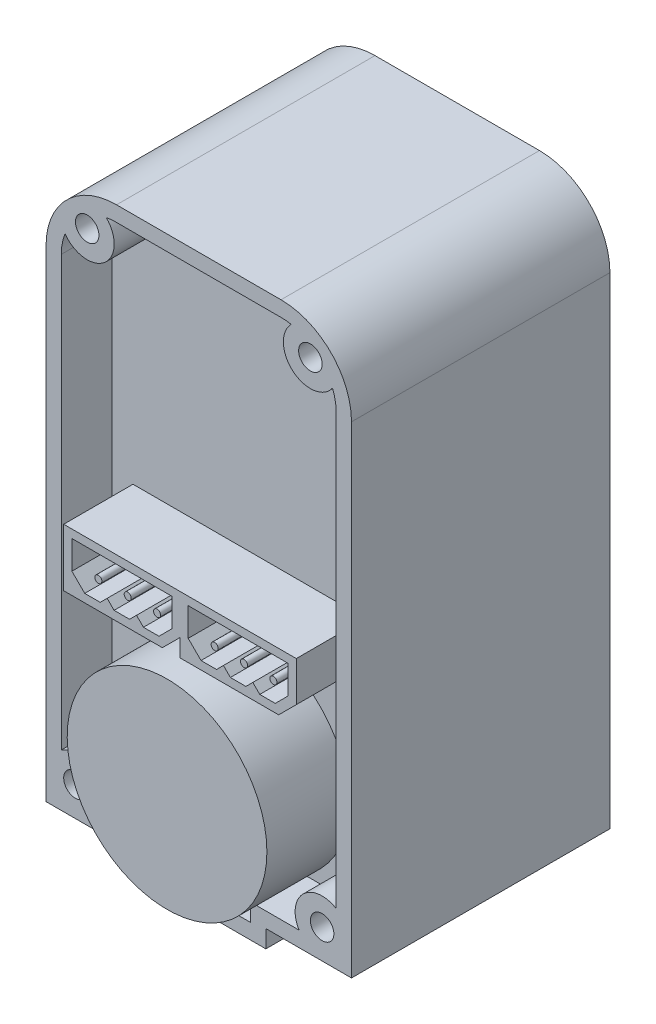
SolidWorks part; units mm, degrees
ref_plane "Front Plane" through (0, 0, 0) normal (0, 0, 1) x (1, 0, 0)
ref_plane "Top Plane" through (0, 0, 0) normal (0, 1, 0) x (1, 0, 0)
ref_plane "Right Plane" through (0, 0, 0) normal (1, 0, 0) x (0, 0, -1)
sketch "Sketch1" plane through (0, 0, 0) normal (0, 0, 1) x (1, 0, 0)
  line L0 (0, -55) -> (0, 55) construction
  line L1 (-7, 26.5) -> (7, 26.5)
  line L2 (-13, 20.5) -> (-13, -20.5)
  line L3 (-13, -20.5) -> (-5.71, -20.5)
  line L4 (13, 20.5) -> (13, -20.5)
  line L5 (55, 0) -> (-55, 0) construction
  line L6 (5.71, -20.5) -> (13, -20.5)
  line L8 (-5.71, -20.5) -> (-5.71, -22)
  line L9 (-5.71, -22) -> (5.71, -22)
  line L10 (5.71, -20.5) -> (5.71, -22)
  arc A0 (13, 20.5) -> (7, 26.5) centre (7, 20.5) ccw
  arc A1 (-7, 26.5) -> (-13, 20.5) centre (-7, 20.5) ccw
  point P4 (0, 26.5)
  point P9 (13, 0)
  point P14 (0, -22)
  point P18 (13, 26.5)
  point P21 (-13, 26.5)
  dimension "D5" = 6
  dimension "D1" = 26
  dimension "D2" = 47
  dimension "D3" = 1.5
  dimension "D4" = 11.42
extrude "Boss-Extrude1" add sketch "Sketch1" along normal mid plane 22
sketch "Sketch2" plane through (0, 0, 11) normal (0, 0, 1) x (1, 0, 0)
  line L0 (-9.5, 23.5) -> (9.5, 23.5) construction
  line L1 (-10.5, -18) -> (10.5, -18) construction
  line L2 (0, -55) -> (0, 55) construction
  line L3 (7, 26.5) -> (-7, 26.5) construction
  circle A0 centre (-9.5, 23.5) radius 1
  circle A1 centre (-10.5, -18) radius 1
  circle A2 centre (10.5, -18) radius 1
  circle A3 centre (9.5, 23.5) radius 1
  point P8 (0, 23.5)
  point P11 (0, -18)
  dimension "D3" = 2
  dimension "D1" = 19
  dimension "D2" = 21
  dimension "D4" = 3
  dimension "D5" = 41.5
extrude "Cut-Extrude1" cut sketch "Sketch2" against normal through all
sketch "Sketch4" plane through (0, 0, 11) normal (0, 0, 1) x (1, 0, 0)
  line L16 (4.41, -19.2) -> (11.7, -19.2)
  line L17 (11.7, -19.2) -> (11.7, 20.5)
  line L18 (7, 25.2) -> (-7, 25.2)
  line L19 (-11.7, 20.5) -> (-11.7, -19.2)
  line L20 (-11.7, -19.2) -> (-4.41, -19.2)
  line L21 (-4.41, -19.2) -> (-4.41, -20.7)
  line L22 (-4.41, -20.7) -> (4.41, -20.7)
  line L23 (4.41, -20.7) -> (4.41, -19.2)
  line L32 (4.41, -19.2) -> (8.5379, -19.2)
  line L33 (11.7, -16.0379) -> (11.7, 20.5)
  line L34 (7, 25.2) -> (-7, 25.2)
  line L35 (-11.7, 20.5) -> (-11.7, -16.0379)
  line L36 (-8.5379, -19.2) -> (-4.41, -19.2)
  line L37 (-4.41, -19.2) -> (-4.41, -20.7)
  line L38 (-4.41, -20.7) -> (4.41, -20.7)
  line L39 (4.41, -20.7) -> (4.41, -19.2)
  arc A16 (11.7, 20.5) -> (7, 25.2) centre (7, 20.5) ccw
  arc A17 (-7, 25.2) -> (-11.7, 20.5) centre (-7, 20.5) ccw
  arc A18 (11.7, 20.5) -> (11.3874, 22.1855) centre (7, 20.5) ccw
  arc A19 (-7, 25.2) -> (-7.8667, 25.1194) centre (-7, 20.5) ccw
  circle A20 centre (-9.5, 23.5) radius 2.3
  arc A21 (-11.3874, 22.1855) -> (-7.8667, 25.1194) centre (-9.5, 23.5) ccw
  circle A23 centre (9.5, 23.5) radius 2.3
  arc A24 (7.8667, 25.1194) -> (11.3874, 22.1855) centre (9.5, 23.5) ccw
  circle A29 centre (-10.5, -18) radius 2.3
  arc A30 (-8.5379, -19.2) -> (-11.7, -16.0379) centre (-10.5, -18) ccw
  arc A31 (-11.3874, 22.1855) -> (-11.7, 20.5) centre (-7, 20.5) ccw
  circle A32 centre (10.5, -18) radius 2.3
  arc A33 (11.7, -16.0379) -> (8.5379, -19.2) centre (10.5, -18) ccw
  arc A34 (7.8667, 25.1194) -> (7, 25.2) centre (7, 20.5) ccw
  dimension "D1" = 1.3
  dimension "D2" = 1.3
  dimension "D3" = 1.3
  dimension "D4" = 1.3
  dimension "D5" = 1.3
extrude "Cut-Extrude2" cut sketch "Sketch4" against normal blind 4.3
sketch "Sketch6" plane through (0, 0, 6.7) normal (0, 0, 1) x (1, 0, 0)
  line L0 (0, -12.1) -> (0, 12.1) construction
  line L1 (-5.71, -22) -> (5.71, -22) construction
  circle A0 centre (0, -12.1) radius 8.5
  dimension "D1" = 17
  dimension "D2" = 9.9
extrude "Boss-Extrude2" add sketch "Sketch6" along normal blind 7
sketch "Sketch7" plane through (0, 0, 6.7) normal (0, 0, 1) x (1, 0, 0)
  line L0 (-1.5, -2.6) -> (0, -1.1)
  line L5 (-9.9, 2.3) -> (9.9, 2.3)
  line L6 (-9.9, 2.3) -> (-9.9, -2.6)
  line L7 (-9.9, -2.6) -> (-1.5, -2.6)
  line L8 (9.9, 2.3) -> (9.9, -1.1)
  line L9 (0, -1.1) -> (0, -2.6)
  line L10 (8.4, -2.6) -> (9.9, -1.1)
  line L11 (0, -2.6) -> (8.4, -2.6)
  line L12 (0, -13.585) -> (0, 13.585) construction
  line L13 (7, 26.5) -> (-7, 26.5) construction
  dimension "D1" = 4.9
  dimension "D2" = 9.9
  dimension "D3" = 45
  dimension "D4" = 24.2
  dimension "D5" = 1.5
extrude "Boss-Extrude3" add sketch "Sketch7" along normal blind 5.9
sketch "Sketch8" plane through (0, 0, 12.6) normal (0, 0, 1) x (1, 0, 0)
  line L0 (-9.2, 1.6) -> (-9.2, -0.8101)
  line L1 (-8.1101, -1.9) -> (-6.7899, -1.9)
  line L2 (-1.7899, -1.9) -> (-0.7, -0.8101)
  line L3 (-0.7, -0.8101) -> (-0.7, 1.6)
  line L4 (-0.7, 1.6) -> (-9.2, 1.6)
  line L5 (9.9, 2.3) -> (-9.9, 2.3) construction
  line L6 (-9.9, 2.3) -> (-9.9, -2.6) construction
  line L7 (0, -1.1) -> (0, -2.6) construction
  line L8 (-1.5, -2.6) -> (0, -1.1) construction
  line L9 (-9.2, -0.8101) -> (-8.1101, -1.9)
  line L10 (-6.7899, -1.9) -> (-6.2, -1.3101)
  line L11 (-6.2, -1.3101) -> (-5.6101, -1.9)
  line L12 (-4.2899, -1.9) -> (-3.7, -1.3101)
  line L13 (-3.7, -1.3101) -> (-3.1101, -1.9)
  line L14 (-3.1101, -1.9) -> (-1.7899, -1.9)
  line L15 (-5.6101, -1.9) -> (-4.2899, -1.9)
  line L16 (0, -2.6) -> (0, 4.1389) construction
  line L17 (5.6101, -1.9) -> (4.2899, -1.9)
  line L18 (3.1101, -1.9) -> (1.7899, -1.9)
  line L19 (3.7, -1.3101) -> (3.1101, -1.9)
  line L20 (4.2899, -1.9) -> (3.7, -1.3101)
  line L21 (6.2, -1.3101) -> (5.6101, -1.9)
  line L22 (6.7899, -1.9) -> (6.2, -1.3101)
  line L23 (9.2, -0.8101) -> (8.1101, -1.9)
  line L24 (0.7, 1.6) -> (9.2, 1.6)
  line L25 (0.7, -0.8101) -> (0.7, 1.6)
  line L26 (1.7899, -1.9) -> (0.7, -0.8101)
  line L27 (8.1101, -1.9) -> (6.7899, -1.9)
  line L28 (9.2, 1.6) -> (9.2, -0.8101)
  point P21 (-7.45, -1.9)
  point P22 (-2.45, -1.9)
  dimension "D1" = 0.7
  dimension "D2" = 3.5
  dimension "D3" = 0.7
  dimension "D4" = 0.7
  dimension "D5" = 0.7
  dimension "D6" = 45
  dimension "D7" = 5
extrude "Cut-Extrude3" cut sketch "Sketch8" against normal blind 4
sketch "Sketch9" plane through (0, 0, 8.6) normal (0, 0, 1) x (1, 0, 0)
  line L0 (-5.6101, -1.9) -> (-4.2899, -1.9) construction
  line L1 (-0.7, 1.6) -> (-9.2, 1.6) construction
  line L2 (0, -2.6) -> (0, 5.4789) construction
  circle A0 centre (-7.45, -0.78) radius 0.3
  circle A1 centre (-4.95, -0.78) radius 0.3
  circle A2 centre (-2.45, -0.78) radius 0.3
  circle A3 centre (2.45, -0.78) radius 0.3
  circle A4 centre (4.95, -0.78) radius 0.3
  circle A5 centre (7.45, -0.78) radius 0.3
  point P10 (-4.95, -1.9)
  dimension "D3" = 0.6
  dimension "D1" = 2.5
  dimension "D2" = 5
  dimension "D4" = 2.38
extrude "Boss-Extrude4" add sketch "Sketch9" along normal blind 3.5
sketch "Sketch10" plane through (0, 0, -11) normal (0, 0, -1) x (-1, 0, 0)
  line L9 (-11.7, -16.0379) -> (-11.7, 20.5) construction
  line L10 (11.7, 20.5) -> (11.7, -16.0379) construction
  line L11 (-7, 25.2) -> (7, 25.2) construction
  line L13 (-11.7, -16.0379) -> (-11.7, 20.5)
  line L14 (11.7, 20.5) -> (11.7, -16.0379)
  line L15 (-7, 25.2) -> (7, 25.2)
  line L35 (13, -19.2) -> (4.41, -19.2)
  line L36 (4.41, -19.2) -> (4.41, -20.7)
  line L37 (-4.41, -20.7) -> (-4.41, -19.2)
  line L38 (4.41, -20.7) -> (-4.41, -20.7)
  line L39 (-4.41, -19.2) -> (-13, -19.2)
  line L40 (8.5379, -19.2) -> (4.41, -19.2)
  line L41 (4.41, -19.2) -> (4.41, -20.7)
  line L42 (-4.41, -20.7) -> (-4.41, -19.2)
  line L43 (4.41, -20.7) -> (-4.41, -20.7)
  line L44 (-4.41, -19.2) -> (-8.5379, -19.2)
  arc A2 (11.7, -16.0379) -> (8.5379, -19.2) centre (10.5, -18) ccw construction
  arc A3 (-8.5379, -19.2) -> (-11.7, -16.0379) centre (-10.5, -18) ccw construction
  arc A4 (-11.3874, 22.1855) -> (-11.7, 20.5) centre (-7, 20.5) ccw construction
  arc A5 (-11.3874, 22.1855) -> (-7.8667, 25.1194) centre (-9.5, 23.5) ccw construction
  arc A6 (-7, 25.2) -> (-7.8667, 25.1194) centre (-7, 20.5) ccw construction
  arc A7 (11.7, 20.5) -> (11.3874, 22.1855) centre (7, 20.5) ccw construction
  arc A8 (7.8667, 25.1194) -> (11.3874, 22.1855) centre (9.5, 23.5) ccw construction
  arc A9 (7.8667, 25.1194) -> (7, 25.2) centre (7, 20.5) ccw construction
  arc A10 (11.7, -16.0379) -> (8.5379, -19.2) centre (10.5, -18) ccw
  arc A11 (-8.5379, -19.2) -> (-11.7, -16.0379) centre (-10.5, -18) ccw
  arc A12 (-11.3874, 22.1855) -> (-11.7, 20.5) centre (-7, 20.5) ccw
  arc A13 (-11.3874, 22.1855) -> (-7.8667, 25.1194) centre (-9.5, 23.5) ccw
  arc A14 (-7, 25.2) -> (-7.8667, 25.1194) centre (-7, 20.5) ccw
  arc A15 (11.7, 20.5) -> (11.3874, 22.1855) centre (7, 20.5) ccw
  arc A16 (7.8667, 25.1194) -> (11.3874, 22.1855) centre (9.5, 23.5) ccw
  arc A17 (7.8667, 25.1194) -> (7, 25.2) centre (7, 20.5) ccw
  dimension "D1" = 1.3
sketch "Sketch11" plane through (0, 0, -11) normal (0, 0, -1) x (-1, 0, 0)
  line L0 (-7, 26.5) -> (7, 26.5) construction
  line L1 (3.3, -3) -> (11.7, -3)
  line L2 (-5, -5) -> (-11.7, -5)
  line L3 (13, 20.5) -> (13, -20.5) construction
  line L8 (4.41, -20.7) -> (4.41, -19.2)
  line L9 (4.41, -19.2) -> (8.5379, -19.2)
  line L10 (11.7, -16.0379) -> (11.7, 20.5)
  line L11 (7, 25.2) -> (-7, 25.2)
  line L12 (-11.7, 20.5) -> (-11.7, -16.0379)
  line L13 (-8.5379, -19.2) -> (-4.41, -19.2)
  line L14 (-4.41, -19.2) -> (-4.41, -20.7)
  line L15 (-4.41, -20.7) -> (4.41, -20.7)
  line L18 (11.7, -3) -> (11.7, 20.5)
  line L19 (7, 25.2) -> (-7, 25.2)
  line L20 (-11.7, 20.5) -> (-11.7, -5)
  arc A0 (-5, -5) -> (0.4794, -2.3561) centre (-5, 2) ccw
  arc A1 (0.4794, -2.3561) -> (3.3, -3) centre (3.3, 3.5) ccw
  arc A8 (11.7, -16.0379) -> (8.5379, -19.2) centre (10.5, -18) ccw
  arc A9 (11.7, 20.5) -> (11.3874, 22.1855) centre (7, 20.5) ccw
  arc A10 (7.8667, 25.1194) -> (11.3874, 22.1855) centre (9.5, 23.5) ccw
  arc A11 (7.8667, 25.1194) -> (7, 25.2) centre (7, 20.5) ccw
  arc A12 (-7, 25.2) -> (-7.8667, 25.1194) centre (-7, 20.5) ccw
  arc A13 (-11.3874, 22.1855) -> (-7.8667, 25.1194) centre (-9.5, 23.5) ccw
  arc A14 (-11.3874, 22.1855) -> (-11.7, 20.5) centre (-7, 20.5) ccw
  arc A15 (-8.5379, -19.2) -> (-11.7, -16.0379) centre (-10.5, -18) ccw
  arc A17 (11.7, 20.5) -> (11.3874, 22.1855) centre (7, 20.5) ccw
  arc A18 (7.8667, 25.1194) -> (11.3874, 22.1855) centre (9.5, 23.5) ccw
  arc A19 (7.8667, 25.1194) -> (7, 25.2) centre (7, 20.5) ccw
  arc A20 (-7, 25.2) -> (-7.8667, 25.1194) centre (-7, 20.5) ccw
  arc A21 (-11.3874, 22.1855) -> (-7.8667, 25.1194) centre (-9.5, 23.5) ccw
  arc A22 (-11.3874, 22.1855) -> (-11.7, 20.5) centre (-7, 20.5) ccw
  dimension "D4" = 6.5
  dimension "D5" = 7
  dimension "D2" = 23
  dimension "D3" = 23.2
  dimension "D6" = 18
  dimension "D7" = 8.4
  dimension "D1" = 0
extrude "Cut-Extrude4" cut sketch "Sketch11" against normal blind 6.34
sketch "Sketch12" plane through (0, 0, -4.66) normal (0, 0, -1) x (-1, 0, 0)
  line L0 (-7, 26.5) -> (7, 26.5) construction
  line L5 (7, 25.2) -> (-7, 25.2)
  line L6 (-11.7, 20.5) -> (-11.7, -5)
  line L7 (-11.7, -5) -> (-5, -5)
  line L8 (3.3, -3) -> (11.7, -3)
  line L9 (11.7, -3) -> (11.7, 20.5)
  line L10 (7, 25.2) -> (-7, 25.2)
  line L11 (-11.7, 20.5) -> (-11.7, 15)
  line L13 (3.3, -3) -> (11.7, -3)
  line L14 (11.7, -3) -> (11.7, 20.5)
  arc A0 (-11.7, 15) -> (-3.1954, 3.7448) centre (0, 15) ccw
  arc A8 (11.7, 20.5) -> (11.3874, 22.1855) centre (7, 20.5) ccw
  arc A9 (7.8667, 25.1194) -> (11.3874, 22.1855) centre (9.5, 23.5) ccw
  arc A10 (7.8667, 25.1194) -> (7, 25.2) centre (7, 20.5) ccw
  arc A11 (-7, 25.2) -> (-7.8667, 25.1194) centre (-7, 20.5) ccw
  arc A12 (-11.3874, 22.1855) -> (-7.8667, 25.1194) centre (-9.5, 23.5) ccw
  arc A13 (-11.3874, 22.1855) -> (-11.7, 20.5) centre (-7, 20.5) ccw
  arc A14 (-5, -5) -> (0.4794, -2.3561) centre (-5, 2) ccw
  arc A15 (0.4794, -2.3561) -> (3.3, -3) centre (3.3, 3.5) ccw
  arc A16 (11.7, 20.5) -> (11.3874, 22.1855) centre (7, 20.5) ccw
  arc A17 (7.8667, 25.1194) -> (11.3874, 22.1855) centre (9.5, 23.5) ccw
  arc A18 (7.8667, 25.1194) -> (7, 25.2) centre (7, 20.5) ccw
  arc A19 (-7, 25.2) -> (-7.8667, 25.1194) centre (-7, 20.5) ccw
  arc A20 (-11.3874, 22.1855) -> (-7.8667, 25.1194) centre (-9.5, 23.5) ccw
  arc A21 (-11.3874, 22.1855) -> (-11.7, 20.5) centre (-7, 20.5) ccw
  arc A23 (-3.1954, 3.7448) -> (3.3, -3) centre (3.3, 3.5) ccw
  dimension "D2" = 11.5
  dimension "D1" = 0
extrude "Cut-Extrude5" cut sketch "Sketch12" against normal offset from surface (6.96 mm away) 13.3 up to face at (10.5, 23.5, -11)
sketch "Sketch14" plane through (0, 0, -4.66) normal (0, 0, -1) x (-1, 0, 0)
  circle A0 centre (-5, 2) radius 0.8
  arc A1 (-5, -5) -> (0.4794, -2.3561) centre (-5, 2) ccw construction
  dimension "D1" = 1.6
extrude "Cut-Extrude6" cut sketch "Sketch14" against normal blind 2
sketch "Sketch15" plane through (0, 0, 2.3) normal (0, 0, -1) x (-1, 0, 0)
  circle A0 centre (3.3, 3.5) radius 1
  arc A1 (-3.1954, 3.7448) -> (3.3, -3) centre (3.3, 3.5) ccw construction
  dimension "D1" = 2
extrude "Cut-Extrude7" cut sketch "Sketch15" against normal blind 2
sketch "Sketch16" plane through (0, 0, 2.3) normal (0, 0, -1) x (-1, 0, 0)
  line L0 (-7, 26.5) -> (7, 26.5) construction
  circle A0 centre (0, 15) radius 3.575
  dimension "D2" = 7.15
  dimension "D1" = 11.5
extrude "Cut-Extrude8" cut sketch "Sketch16" against normal blind 3
sketch "Sketch17" plane through (0, 0, -11) normal (0, 0, -1) x (-1, 0, 0)
  line L8 (4.41, -20.7) -> (4.41, -19.2)
  line L9 (4.41, -19.2) -> (8.5379, -19.2)
  line L10 (11.7, -16.0379) -> (11.7, 20.5)
  line L11 (7, 25.2) -> (-7, 25.2)
  line L12 (-11.7, 20.5) -> (-11.7, -16.0379)
  line L13 (-8.5379, -19.2) -> (-4.41, -19.2)
  line L14 (-4.41, -19.2) -> (-4.41, -20.7)
  line L15 (-4.41, -20.7) -> (4.41, -20.7)
  line L16 (4.41, -20.7) -> (4.41, -19.2)
  line L17 (4.41, -19.2) -> (8.5379, -19.2)
  line L18 (11.7, -16.0379) -> (11.7, 20.5)
  line L19 (7, 25.2) -> (-7, 25.2)
  line L20 (-11.7, 20.5) -> (-11.7, -16.0379)
  line L21 (-8.5379, -19.2) -> (-4.41, -19.2)
  line L22 (-4.41, -19.2) -> (-4.41, -20.7)
  line L23 (-4.41, -20.7) -> (4.41, -20.7)
  arc A8 (11.7, -16.0379) -> (8.5379, -19.2) centre (10.5, -18) ccw
  arc A9 (11.7, 20.5) -> (11.3874, 22.1855) centre (7, 20.5) ccw
  arc A10 (7.8667, 25.1194) -> (11.3874, 22.1855) centre (9.5, 23.5) ccw
  arc A11 (7.8667, 25.1194) -> (7, 25.2) centre (7, 20.5) ccw
  arc A12 (-7, 25.2) -> (-7.8667, 25.1194) centre (-7, 20.5) ccw
  arc A13 (-11.3874, 22.1855) -> (-7.8667, 25.1194) centre (-9.5, 23.5) ccw
  arc A14 (-11.3874, 22.1855) -> (-11.7, 20.5) centre (-7, 20.5) ccw
  arc A15 (-8.5379, -19.2) -> (-11.7, -16.0379) centre (-10.5, -18) ccw
  arc A16 (11.7, -16.0379) -> (8.5379, -19.2) centre (10.5, -18) ccw
  arc A17 (11.7, 20.5) -> (11.3874, 22.1855) centre (7, 20.5) ccw
  arc A18 (7.8667, 25.1194) -> (11.3874, 22.1855) centre (9.5, 23.5) ccw
  arc A19 (7.8667, 25.1194) -> (7, 25.2) centre (7, 20.5) ccw
  arc A20 (-7, 25.2) -> (-7.8667, 25.1194) centre (-7, 20.5) ccw
  arc A21 (-11.3874, 22.1855) -> (-7.8667, 25.1194) centre (-9.5, 23.5) ccw
  arc A22 (-11.3874, 22.1855) -> (-11.7, 20.5) centre (-7, 20.5) ccw
  arc A23 (-8.5379, -19.2) -> (-11.7, -16.0379) centre (-10.5, -18) ccw
  dimension "D1" = 0
extrude "Cut-Extrude9" cut sketch "Sketch17" against normal blind 0.7
sketch "Sketch18" plane through (0, 0, -10.3) normal (0, 0, -1) x (-1, 0, 0)
  line L0 (-5, -5) -> (-11.7, -5) construction
  line L3 (-4.4621, -20.6) -> (4.4621, -20.6)
  line L5 (-5, -5) -> (-6.4614, -5)
  arc A0 (4.4621, -20.6) -> (3.0426, -2.9949) centre (0, -12.1) ccw
  circle A1 centre (0, -12.1) radius 8.5 construction
  arc A2 (-6.4614, -5) -> (-4.4621, -20.6) centre (0, -12.1) ccw
  arc A3 (-5, -5) -> (0.4794, -2.3561) centre (-5, 2) ccw construction
  arc A4 (-5, -5) -> (0.4794, -2.3561) centre (-5, 2) ccw
  arc A5 (-3.1954, 3.7448) -> (3.3, -3) centre (3.3, 3.5) ccw construction
  arc A6 (0.4794, -2.3561) -> (3.0426, -2.9949) centre (3.3, 3.5) ccw
  dimension "D1" = 19.2
extrude "Boss-Extrude5" add sketch "Sketch18" along normal blind 2
sketch "Sketch19" plane through (0, 0, -12.3) normal (0, 0, -1) x (-1, 0, 0)
  circle A0 centre (0, -12.1) radius 0.75
  arc A1 (-6.4614, -5) -> (-4.4621, -20.6) centre (0, -12.1) ccw construction
  dimension "D1" = 1.5
extrude "Boss-Extrude6" add sketch "Sketch19" along normal blind 5
sketch "Sketch20" plane through (0, 0, -17.3) normal (0, 0, -1) x (-1, 0, 0)
  line L0 (0, -12.1) -> (-0.3522, -10.9006) construction
  line L1 (-0.3522, -10.9006) -> (0, -10.475)
  line L2 (0, -10.475) -> (0.3522, -10.9006)
  line L3 (0.3522, -10.9006) -> (0, -12.1) construction
  line L4 (0.8785, -10.733) -> (0.9447, -11.2814)
  line L5 (0.3522, -10.9006) -> (0.8785, -10.733)
  line L6 (1.4782, -11.425) -> (1.2373, -11.9221)
  line L7 (0.9447, -11.2814) -> (1.4782, -11.425)
  line L8 (1.6085, -12.3313) -> (1.137, -12.6193)
  line L9 (1.2373, -11.9221) -> (1.6085, -12.3313)
  line L10 (1.2281, -13.1641) -> (0.6758, -13.1516)
  line L11 (1.137, -12.6193) -> (1.2281, -13.1641)
  line L12 (0.4578, -13.6592) -> (0, -13.35)
  line L13 (0.6758, -13.1516) -> (0.4578, -13.6592)
  line L14 (-0.4578, -13.6592) -> (-0.6758, -13.1516)
  line L15 (0, -13.35) -> (-0.4578, -13.6592)
  line L16 (-1.2281, -13.1641) -> (-1.137, -12.6193)
  line L17 (-0.6758, -13.1516) -> (-1.2281, -13.1641)
  line L18 (-1.6085, -12.3313) -> (-1.2373, -11.9221)
  line L19 (-1.137, -12.6193) -> (-1.6085, -12.3313)
  line L20 (-1.4782, -11.425) -> (-0.9447, -11.2814)
  line L21 (-1.2373, -11.9221) -> (-1.4782, -11.425)
  line L22 (-0.8785, -10.733) -> (-0.3522, -10.9006)
  line L23 (-0.9447, -11.2814) -> (-0.8785, -10.733)
  circle A0 centre (0, -12.1) radius 1.25 construction
  circle A1 centre (0, -12.1) radius 0.75 construction
  circle A2 centre (0, -12.1) radius 1.625 construction
  point P41 (0, -12.1)
  dimension "D2" = 3.25
  dimension "D3" = 2.5
  dimension "D1" = 32.727
  dimension "D4" = 11
extrude "Boss-Extrude7" add sketch "Sketch20" against normal blind 2.7
sketch "Sketch21" plane through (0, 0, -12.3) normal (0, 0, -1) x (-1, 0, 0)
  line L0 (-13, -20.5) -> (-13, 20.5) construction
  line L1 (-7, 26.5) -> (7, 26.5) construction
  circle A0 centre (0.8, -4.7) radius 0.8
  dimension "D3" = 1.6
  dimension "D1" = 13.8
  dimension "D2" = 31.2
extrude "Cut-Extrude10" cut sketch "Sketch21" against normal blind 1
sketch "Sketch22" plane through (0, 0, 2.3) normal (0, 0, -1) x (-1, 0, 0)
  circle A0 centre (0, 15) radius 5.6
  circle A1 centre (0, 15) radius 3.575 construction
  circle A2 centre (0, 15) radius 3.575
  dimension "D1" = 11.2
extrude "Boss-Extrude8" add sketch "Sketch22" along normal blind 3
